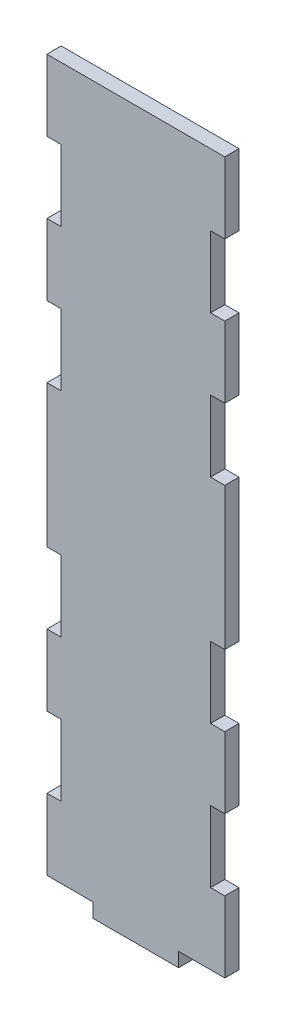
SolidWorks part; units mm, degrees
ref_plane "Plano frontal" through (0, 0, 0) normal (0, 0, 1) x (1, 0, 0)
ref_plane "Plano superior" through (0, 0, 0) normal (0, 1, 0) x (1, 0, 0)
ref_plane "Plano direito" through (0, 0, 0) normal (1, 0, 0) x (0, 0, -1)
sketch "Esboço1" plane through (0, 0, 0) normal (0, 0, 1) x (1, 0, 0)
  line L0 (0, 100) -> (0, -100) construction
  line L1 (-50, -100) -> (-37, -100)
  line L2 (-50, -100) -> (-50, 100)
  line L3 (-50, 100) -> (50, 100)
  line L4 (50, -100) -> (50, 100)
  line L5 (-50, -100) -> (50, 100) construction
  line L6 (-50, 100) -> (50, -100) construction
  line L7 (-50, 0) -> (50, 0) construction
  line L8 (-37, -100) -> (-37, -104)
  line L9 (-37, -104) -> (-13, -104)
  line L10 (-13, -104) -> (-13, -100)
  line L11 (13, -104) -> (13, -100)
  line L12 (37, -104) -> (13, -104)
  line L13 (37, -100) -> (37, -104)
  line L14 (-13, -100) -> (13, -100)
  line L15 (37, -100) -> (50, -100)
  point P0 (0, 0)
  dimension "D1" = 100
  dimension "D2" = 200
  dimension "D3" = 4
  dimension "D4" = 24
  dimension "D5" = 13
extrude "Ressalto-extrusão1" add sketch "Esboço1" along normal blind 4
sketch "Esboço2" plane through (0, 0, 4) normal (0, 0, 1) x (1, 0, 0)
  line L0 (0, -100) -> (0, 100)
  line L1 (-13, -100) -> (13, -100) construction
  line L2 (50, 100) -> (-50, 100) construction
  line L3 (0, 80) -> (4, 80)
  line L4 (4, 80) -> (4, 60)
  line L5 (4, 60) -> (0, 60)
  line L6 (-50, 0) -> (50, 0) construction
  line L7 (-50, 100) -> (-50, -100) construction
  line L8 (50, -100) -> (50, 100) construction
  line L9 (0, 40) -> (4, 40)
  line L10 (4, 40) -> (4, 20)
  line L11 (4, 20) -> (0, 20)
  line L12 (0, 40) -> (0, 20)
  line L13 (0, 80) -> (0, 60)
  line L14 (0, -80) -> (4, -80)
  line L15 (4, -80) -> (4, -60)
  line L16 (4, -60) -> (0, -60)
  line L17 (0, -80) -> (0, -60)
  line L18 (0, -40) -> (4, -40)
  line L19 (4, -40) -> (4, -20)
  line L20 (4, -20) -> (0, -20)
  line L21 (0, -40) -> (0, -20)
  line M11 (50, 100) -> (-50, 100)
  line M12 (-50, 100) -> (-50, -100)
  line M13 (-50, -100) -> (-37, -100)
  line M14 (-37, -100) -> (-37, -104)
  line M15 (-37, -104) -> (-13, -104)
  line M16 (-13, -104) -> (-13, -100)
  line M17 (-13, -100) -> (13, -100)
  dimension "D1" = 4
  dimension "D2" = 20
  dimension "D3" = 20
  dimension "D4" = 20
extrude "Corte-extrusão1" cut sketch "Esboço2" against normal through all contours L6 L0 M12 M11 | L6 L0 M12 M13 M14 M15 M16 M17 | L5 L4 L3 L0 | L19 L20 L0 L18 | L15 L16 L0 L14 | L10 L11 L12 L9
sketch "Esboço3" plane through (0, 0, 4) normal (0, 0, 1) x (1, 0, 0)
  line L0 (0, 0) -> (50, 0) construction
  line L1 (50, -100) -> (50, 100) construction
  line L2 (50, 80) -> (46, 80)
  line L3 (46, 80) -> (46, 60)
  line L4 (46, 60) -> (50, 60)
  line L5 (50, 60) -> (50, 80)
  line L6 (50, 40) -> (46, 40)
  line L7 (46, 40) -> (46, 20)
  line L8 (46, 20) -> (50, 20)
  line L9 (50, 20) -> (50, 40)
  line L10 (50, 100) -> (0, 100) construction
  line L11 (46, -60) -> (50, -60)
  line L12 (46, -80) -> (46, -60)
  line L13 (50, -80) -> (46, -80)
  line L14 (50, -60) -> (50, -80)
  line L15 (46, -20) -> (50, -20)
  line L16 (46, -40) -> (46, -20)
  line L17 (50, -40) -> (46, -40)
  line L18 (50, -20) -> (50, -40)
  dimension "D1" = 4
  dimension "D2" = 20
  dimension "D3" = 20
  dimension "D4" = 20
extrude "Corte-extrusão2" cut sketch "Esboço3" against normal through all
